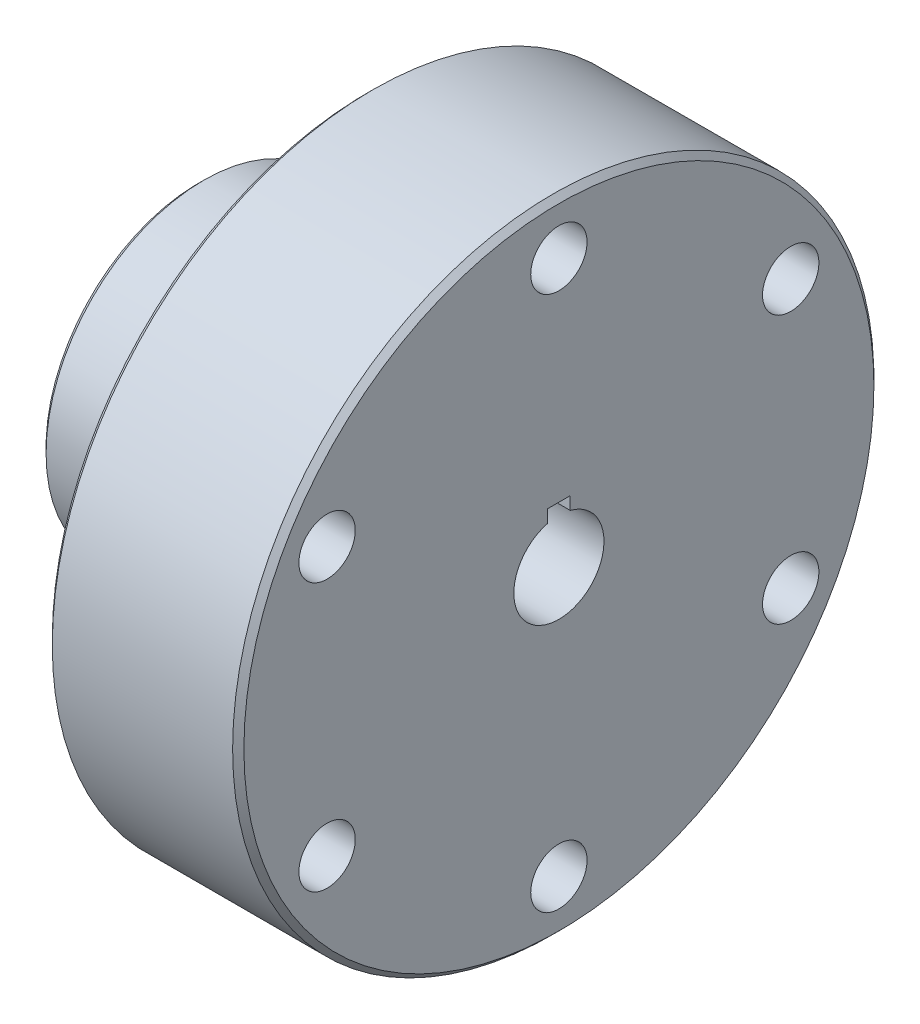
SolidWorks part; units mm, degrees
ref_plane "Plan de face" through (0, 0, 0) normal (0, 0, 1) x (1, 0, 0)
ref_plane "Plan de dessus" through (0, 0, 0) normal (0, 1, 0) x (1, 0, 0)
ref_plane "Plan de droite" through (0, 0, 0) normal (1, 0, 0) x (0, 0, -1)
sketch "Esquisse1" plane through (0, 0, 0) normal (0, 0, 1) x (1, 0, 0)
  line L0 (-36.38, 0) -> (27.4382, 0) construction
  line L1 (-15, 4) -> (-15, 14)
  line L2 (-15, 14) -> (-5, 14)
  line L3 (-5, 14) -> (-5, 15)
  line L4 (-5, 15) -> (0, 15)
  line L5 (0, 15) -> (0, 28.45)
  line L6 (0, 28.45) -> (17, 28.45)
  line L7 (17, 28.45) -> (17, 4)
  line L8 (17, 4) -> (-15, 4)
  dimension "D1" = 32
  dimension "D2" = 28.45
  dimension "D3" = 5
  dimension "D4" = 10
  dimension "D5" = 14
  dimension "D6" = 15
  dimension "D7" = 4
revolve "Révolution1" add sketch "Esquisse1" angle 360 about L0
sketch "Esquisse2" plane through (0, 0, 0) normal (-1, 0, 0) x (0, 0, 1)
  line L0 (0, 37.888) -> (0, -36.3953) construction
  line L1 (-43.0472, 0) -> (49.1338, 0) construction
  circle A0 centre (0, 23.75) radius 2.5
  circle A1 centre (20.5681, 11.875) radius 2.5
  circle A2 centre (20.5681, -11.875) radius 2.5
  circle A3 centre (0, -23.75) radius 2.5
  circle A4 centre (-20.5681, -11.875) radius 2.5
  circle A5 centre (-20.5681, 11.875) radius 2.5
  point P20 (0, 0)
  dimension "D2" = 5
  dimension "D1" = 23.75
  dimension "D3" = 6
extrude "Enlèv. mat.-Extru.1" cut sketch "Esquisse2" against normal through all
sketch "Esquisse3" plane through (-15, 0, 0) normal (-1, 0, 0) x (0, 0, 1)
  line L0 (0, 32.4747) -> (0, -1.7657) construction
  line L2 (-1, 5) -> (1, 5)
  line L3 (-1, 5) -> (-1, 2.2622)
  line L4 (-1, 2.2622) -> (1, 2.2622)
  line L5 (1, 5) -> (1, 2.2622)
  point P7 (0, 5)
  dimension "D1" = 5
  dimension "D2" = 2
extrude "Enlèv. mat.-Extru.2" cut sketch "Esquisse3" against normal through all
ref_plane "Plan1" through (0, 0, 0) normal (0, 0, 1) x (1, 0, 0)
sketch "Esquisse4" plane through (0, 0, 0) normal (0, 0, 1) x (1, 0, 0)
  line L0 (-36.38, 0) -> (27.4382, 0) construction
  line L1 (-15, 14) -> (-15, -14) construction
  circle A0 centre (-10, 0) radius 3
  dimension "D1" = 5
extrude "Enlèv. mat.-Extru.3" cut sketch "Esquisse4" against normal blind 20
chamfer "Chanfrein1" distance 0.5 angle 45 4 edges at (17, 0, 28.45) (0, 0, 28.45) (-5, 0, 15) (-15, 0, 14)
